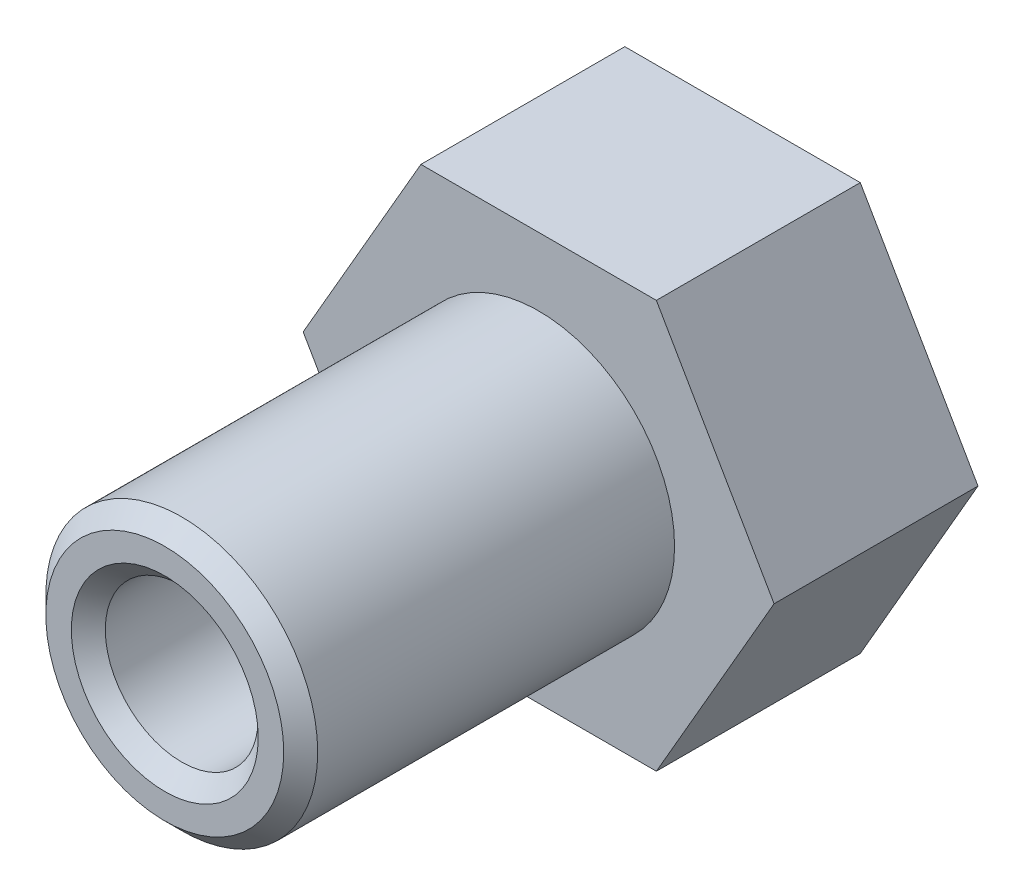
SolidWorks part; units mm, degrees
ref_plane "前视基准面" through (0, 0, 0) normal (0, 0, 1) x (1, 0, 0)
ref_plane "上视基准面" through (0, 0, 0) normal (0, 1, 0) x (1, 0, 0)
ref_plane "右视基准面" through (0, 0, 0) normal (1, 0, 0) x (0, 0, -1)
sketch "草图1" plane through (0, 0, 0) normal (0, 0, 1) x (1, 0, 0)
  line L1 (-6.9282, -12) -> (6.9282, -12)
  line L2 (6.9282, -12) -> (13.8564, 0)
  line L3 (13.8564, 0) -> (6.9282, 12)
  line L4 (6.9282, 12) -> (-6.9282, 12)
  line L5 (-6.9282, 12) -> (-13.8564, 0)
  line L6 (-13.8564, 0) -> (-6.9282, -12)
  circle A0 centre (0, 0) radius 12 construction
  dimension "D1" = 24
extrude "拉伸1" add sketch "草图1" along normal blind 12
sketch "草图2" plane through (0, 0, 12) normal (0, 0, 1) x (1, 0, 0)
  circle A0 centre (0, 0) radius 8
  dimension "D1" = 16
extrude "拉伸2" add sketch "草图2" along normal blind 22
cosmetic thread "装饰螺纹线1" parameters "D2"=14
sketch "草图3" plane through (0, 0, 0) normal (0, 0, -1) x (-1, 0, 0)
  circle A0 centre (0, 0) radius 4.5
  dimension "D1" = 9
extrude "拉伸3" cut sketch "草图3" against normal through all
chamfer "倒角1" distance 1 angle 45 1 edges at (8, 0, 34)
chamfer "倒角2" distance 1 angle 45 1 edges at (-4.5, 0, 34)
